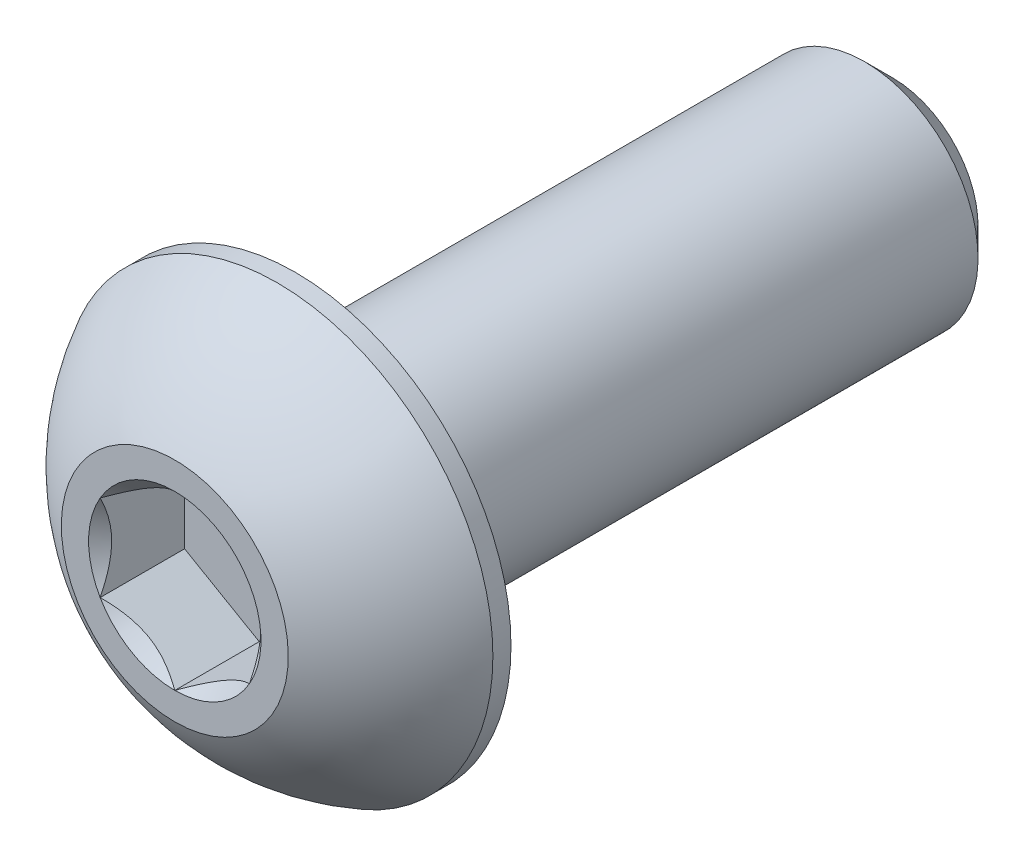
SolidWorks part; units mm, degrees
material "AISI 4130 Steel, annealed at 865C"
ref_plane "Front" through (0, 0, 0) normal (0, 0, 1) x (1, 0, 0)
ref_plane "Top" through (0, 0, 0) normal (0, 1, 0) x (1, 0, 0)
ref_plane "Right" through (0, 0, 0) normal (1, 0, 0) x (0, 0, -1)
sketch "Sketch1" plane through (0, 0, 0) normal (1, 0, 0) x (0, 0, -1)
  line L2 (2.5654, 2.413) -> (15.2654, 2.413)
  line L3 (15.2654, 2.413) -> (15.2654, 0)
  line L4 (15.2654, 0) -> (2.5654, 0)
  line L6 (2.1806, 4.5847) -> (2.5654, 4.5847) construction
  line L7 (15.2654, 2.413) -> (15.2654, -2.413) construction
  line L8 (0, 0) -> (2.5654, 0) construction
  line L9 (2.5654, 4.5847) -> (2.5654, -4.5847) construction
  line L11 (2.5654, 2.413) -> (2.5654, 0)
  line L13 (0, 1.5875) -> (0, -1.5875) construction
  line L14 (0, 1.5875) -> (0, 2.413) construction
  arc A3 (0, 2.413) -> (2.1806, 4.5847) centre (4.5749, 0) cw construction
  dimension "D1" = 0.3848
revolve "Revolve1" add sketch "Sketch1" angle 360 mid plane about L4
sketch "Sketch3" plane through (0, 0, -15.2654) normal (0, 0, -1) x (-1, 0, 0)
  circle A0 centre (0, 0) radius 2.413
curve "Helix/Spiral1" pitch 0.7937 height 13.4937 turns 17
sketch "Sketch2" plane through (0, 0, 0) normal (1, 0, 0) x (0, 0, -1)
  line L0 (15.2654, 2.413) -> (15.9599, 2.413)
  line L1 (15.9599, 2.413) -> (15.6623, 1.8974)
  line L2 (15.6623, 1.8974) -> (15.5631, 1.8974)
  line L3 (15.5631, 1.8974) -> (15.2654, 2.413)
  line L4 (15.4142, 2.1552) -> (15.8111, 2.1552) construction
  dimension "D1" = 60
  dimension "D2" = 0.0992
  dimension "D3" = 0.3969
chamfer "Chamfer1" distance 0.5953 angle 45 1 edges at (0, 2.413, -15.2654)
sketch "Sketch7" plane through (0, 0, 0) normal (1, 0, 0) x (0, 0, -1)
  line L6 (2.1806, 4.5847) -> (2.5654, 4.5847) construction
  line L8 (0, 0) -> (2.5654, 0) construction
  line L11 (2.5654, 4.5847) -> (2.5654, -4.5847) construction
  line L12 (2.1806, 4.5847) -> (2.5654, 4.5847)
  line L13 (0, 0) -> (2.5654, 0)
  line L14 (0, 1.5875) -> (0, -1.5875) construction
  line L15 (2.5654, 4.5847) -> (2.5654, 0)
  line L16 (0, 2.413) -> (0, 0)
  arc A2 (2.1806, 4.5847) -> (0, 2.413) centre (4.5749, 0) ccw construction
  arc A3 (2.1806, 4.5847) -> (0, 2.413) centre (4.5749, 0) ccw
revolve "Revolve2" add sketch "Sketch7" angle 360 mid plane about L13
sketch "Sketch5" plane through (0, 0, 0) normal (0, 0, 1) x (1, 0, 0)
  line L1 (1.5875, -0.9165) -> (1.5875, 0.9165)
  line L2 (1.5875, 0.9165) -> (0, 1.8331)
  line L3 (0, 1.8331) -> (-1.5875, 0.9165)
  line L4 (-1.5875, 0.9165) -> (-1.5875, -0.9165)
  line L5 (-1.5875, -0.9165) -> (0, -1.8331)
  line L6 (0, -1.8331) -> (1.5875, -0.9165)
  circle A0 centre (0, 0) radius 1.5875 construction
extrude "Cut-Extrude2" cut sketch "Sketch5" against normal blind 1.7958
sketch "Sketch6" plane through (0, 0, 0) normal (0, 0, 1) x (1, 0, 0)
  circle A0 centre (0, 0) radius 1.8331
extrude "Cut-Extrude3" cut sketch "Sketch6" against normal blind 1.7958 draft 45
sketch "Sketch10" plane through (0, 0, 0) normal (1, 0, 0) x (0, 0, -1)
  line L0 (15.2654, 2.413) -> (15.2654, -2.413) construction
  point P0 (14.0748, -2.413)
  dimension "D1" = 1.1906
equation "\"D3@Helix/Spiral1\" = \"Lg@Sketch1\" + \"D4@Helix/Spiral1\""
equation "\"D2@Sketch2\" = \"D4@Helix/Spiral1\" * .125"
equation "\"D3@Sketch2\" = \"D4@Helix/Spiral1\" * .5"
equation "\"D1@Chamfer1\" = \"D4@Helix/Spiral1\" * .75"
equation "\"D1@Cut-Extrude2\" = \"Head Ht@Sketch1\" * .7"
equation "\"D1@Sketch1\" = \"Head Ht@Sketch1\" * .15"
equation "\"D1@Sketch10\" = \"D4@Helix/Spiral1\" * 1.5"
equation "\"D1@Cut-Extrude3\" = \"D1@Cut-Extrude2\""
